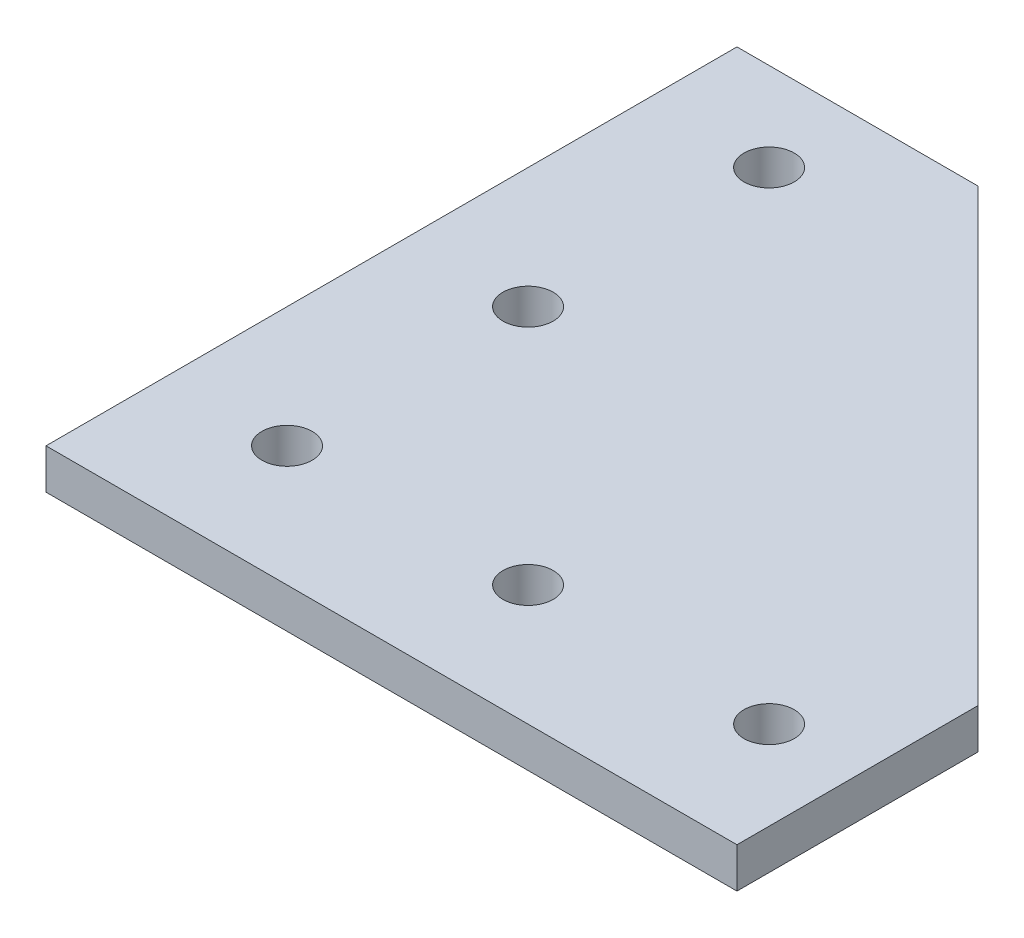
SolidWorks part; units mm, degrees
ref_plane "Front Plane" through (0, 0, 0) normal (0, 0, 1) x (1, 0, 0)
ref_plane "Top Plane" through (0, 0, 0) normal (0, 1, 0) x (1, 0, 0)
ref_plane "Right Plane" through (0, 0, 0) normal (1, 0, 0) x (0, 0, -1)
sketch "Sketch1" plane through (0, 0, 0) normal (0, 1, 0) x (1, 0, 0)
  line L0 (0, 0) -> (0, 76.2) construction
  line L1 (0, 76.2) -> (0, 0) construction
  line L2 (0, 0) -> (76.2, 0) construction
  line L3 (-19.05, 90.17) -> (19.05, 90.17)
  line L4 (0, 90.17) -> (0, 76.2) construction
  line L5 (-19.05, 90.17) -> (-19.05, -19.05)
  line L6 (-19.05, -19.05) -> (90.17, -19.05)
  line L7 (90.17, -19.05) -> (90.17, 19.05)
  line L8 (76.2, 0) -> (90.17, 0) construction
  line L9 (19.05, 90.17) -> (90.17, 19.05)
  circle A0 centre (0, 0) radius 3.9688
  circle A1 centre (38.1, 0) radius 3.9687
  circle A2 centre (76.2, 0) radius 3.9687
  circle A3 centre (0, 38.1) radius 3.9688
  circle A4 centre (0, 76.2) radius 3.9687
  dimension "D1" = 7.9375
  dimension "D2" = 76.2
  dimension "D3" = 76.2
  dimension "D4" = 38.1
  dimension "D5" = 13.97
  dimension "D6" = 38.1
  dimension "D7" = 13.97
extrude "Boss-Extrude3" add sketch "Sketch1" along normal blind 6.35
